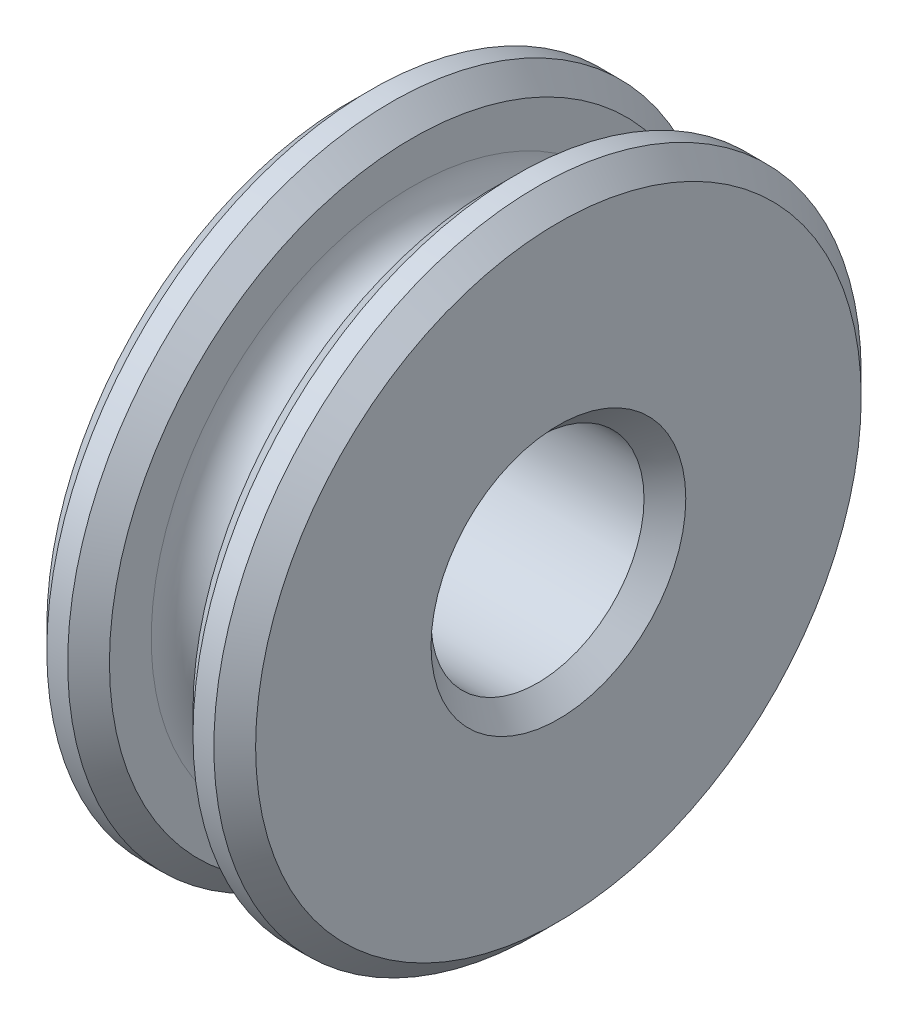
SolidWorks part; units mm, degrees
ref_plane "Plan de face" through (0, 0, 0) normal (1, 0, 0) x (0, 1, 0)
ref_plane "Plan de dessus" through (0, 0, 0) normal (0, 0, 1) x (0, 1, 0)
ref_plane "Plan de droite" through (0, 0, 0) normal (0, 1, 0) x (-1, 0, 0)
sketch "Esquisse1" plane through (0, 0, 0) normal (0, 0, 1) x (0, 1, 0)
  line L0 (0, 0) -> (0, 24.3799) construction
  line L1 (5.1, 0) -> (15.5, 0)
  line L2 (15.5, 0) -> (15.5, 3)
  line L3 (15.5, 3) -> (12.5, 3)
  line L4 (12.5, 3) -> (12.5, 7)
  line L5 (12.5, 7) -> (15.5, 7)
  line L6 (15.5, 7) -> (15.5, 10)
  line L7 (15.5, 10) -> (5.1, 10)
  line L8 (5.1, 10) -> (5.1, 0)
  circle A0 centre (12.5, 5) radius 2
  point P11 (5.1, 5)
  dimension "D1" = 4
  dimension "D2" = 3
  dimension "D3" = 10.2
  dimension "D4" = 25
  dimension "D5" = 3
revolve "Révolution1" add sketch "Esquisse1" angle 360 about L0
chamfer "Chanfrein1" distance 1 angle 45 6 edges at (0, 0, -5.1) (0, 0, -15.5) (-3, 0, -15.5) (-7, 0, -15.5) (-10, 0, -15.5) (-10, 0, -5.1)
